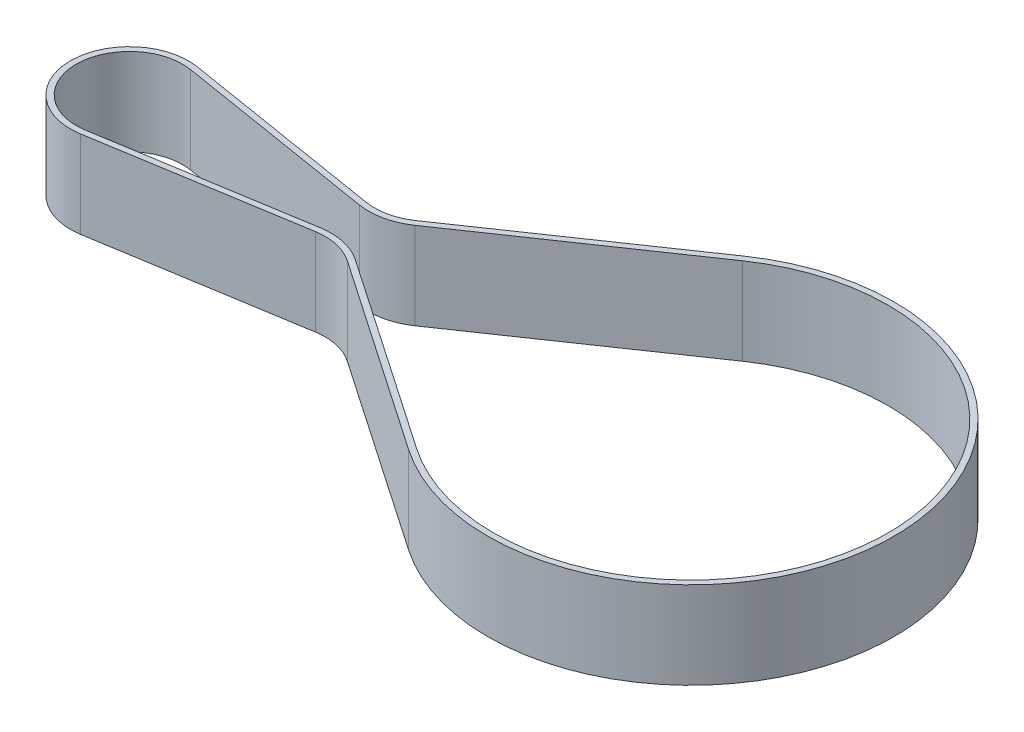
SolidWorks part; units mm, degrees
ref_plane "Front Plane" through (0, 0, 0) normal (0, 0, 1) x (1, 0, 0)
ref_plane "Top Plane" through (0, 0, 0) normal (0, 1, 0) x (1, 0, 0)
ref_plane "Right Plane" through (0, 0, 0) normal (1, 0, 0) x (0, 0, -1)
sketch "Sketch1" plane through (0, 0, 0) normal (0, 1, 0) x (1, 0, 0)
  line L0 (-61.8494, 6.8699) -> (-27.0444, 1.2083)
  line L1 (-63.3217, -2.1811) -> (33.4583, -2.1811)
  line L2 (-26.8838, 2.1954) -> (-61.6888, 7.8569)
  line L3 (-61.8494, -11.2322) -> (-27.0444, -5.5706)
  line L4 (-26.8838, -6.5576) -> (-61.6888, -12.2192)
  line L5 (-19.8117, 3.7729) -> (13.6905, 26.702)
  line L6 (13.6905, 26.702) -> (14.2553, 25.8767)
  line L7 (14.2553, 25.8767) -> (-19.2469, 2.9476)
  line L8 (-19.2469, -7.3099) -> (14.2553, -30.239)
  line L9 (14.2553, -30.239) -> (13.6905, -31.0642)
  line L10 (13.6905, -31.0642) -> (-19.8117, -8.1351)
  circle A0 centre (-63.3217, -2.1811) radius 9.17
  circle A1 centre (-63.3217, -2.1811) radius 10.17
  circle A2 centre (-25.3184, -16.1811) radius 9.75
  circle A3 centre (-25.3184, 11.8189) radius 9.75
  circle A4 centre (-25.3184, 11.8189) radius 10.75
  circle A5 centre (-25.3184, -16.1811) radius 10.75
  circle A6 centre (33.4583, -2.1811) radius 34
  circle A7 centre (33.4583, -2.1811) radius 35
extrude "Boss-Extrude1" add sketch "Sketch1" along normal blind 15 contours A1 L3 A0 L0 | A5 L3 A1 L4 | A4 L2 A1 L0 | A4 L5 A3 L2 | L10 A5 L4 A2 | A7 L5 A4 L7 | A7 L8 A5 L10 | L8 A7 L9 | L9 A7 L6 A6 | L6 A7 L7
